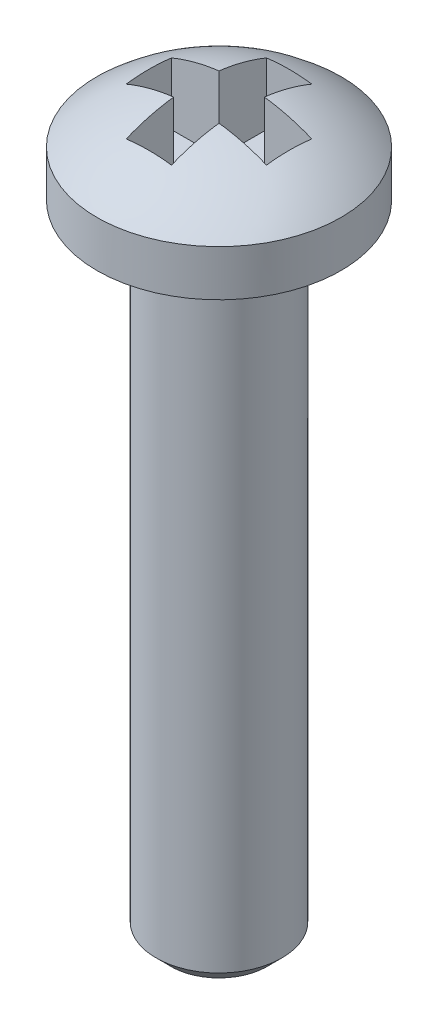
SolidWorks part; units mm, degrees
ref_plane "Front Plane" through (0, 0, 0) normal (0, 0, 1) x (1, 0, 0)
ref_plane "Top Plane" through (0, 0, 0) normal (0, 1, 0) x (1, 0, 0)
ref_plane "Right Plane" through (0, 0, 0) normal (1, 0, 0) x (0, 0, -1)
sketch "Sketch1" plane through (0, 0, 0) normal (0, 0, 1) x (1, 0, 0)
  line L0 (0, 0) -> (0, 52.7449) construction
  line L1 (0, 12.7127) -> (0, 0)
  line L2 (0, 0) -> (0.8382, 0)
  line L3 (1.0922, 0.254) -> (1.0922, 11.1125)
  line L4 (1.0922, 11.1125) -> (2.1209, 11.1125)
  line L5 (2.1209, 11.1125) -> (2.1209, 11.9126)
  line L6 (1.0922, 11.1125) -> (1.0922, 12.7127) construction
  line L7 (0, 12.7127) -> (1.0922, 12.7127) construction
  line L8 (0.8382, 0) -> (1.0922, 0.254)
  arc A0 (0, 12.7127) -> (2.1209, 11.9126) centre (0, 9.5016) cw
  point P5 (1.0922, 0)
  point P11 (1.0922, 11.9126)
  dimension "D1" = 4.2418
  dimension "D2" = 1.6002
  dimension "D3" = 2.1844
  dimension "D4" = 11.1125
revolve "Revolve1" add sketch "Sketch1" angle 360 about L0
ref_plane "Plane1" through (0, 12.7127, 0) normal (0, 1, 0) x (1, 0, 0)
sketch "Sketch2" plane through (0, 12.7127, 0) normal (0, 1, 0) x (1, 0, 0)
  line L0 (-0.3937, 0.3937) -> (-0.3937, 1.2192)
  line L1 (-0.3937, 1.2192) -> (0.3937, 1.2192)
  line L2 (0.3937, 1.2192) -> (0.3937, 0.3937)
  line L3 (0.3937, 0.3937) -> (1.2192, 0.3937)
  line L4 (1.2192, 0.3937) -> (1.2192, -0.3937)
  line L5 (1.2192, -0.3937) -> (0.3937, -0.3937)
  line L6 (0.3937, -0.3937) -> (0.3937, -1.2192)
  line L7 (0.3937, -1.2192) -> (-0.3937, -1.2192)
  line L8 (-0.3937, -1.2192) -> (-0.3937, -0.3937)
  line L9 (-0.3937, -0.3937) -> (-1.2192, -0.3937)
  line L10 (-1.2192, -0.3937) -> (-1.2192, 0.3937)
  line L11 (-1.2192, 0.3937) -> (-0.3937, 0.3937)
  point P11 (1.2192, 0)
  point P14 (0, -1.2192)
  dimension "D1" = 0.7874
  dimension "D2" = 1.2192
extrude "Cut-Extrude1" cut sketch "Sketch2" against normal offset from surface (1.3462 mm away) 0.254 up to face at (0, 11.1125, -2.1209)
